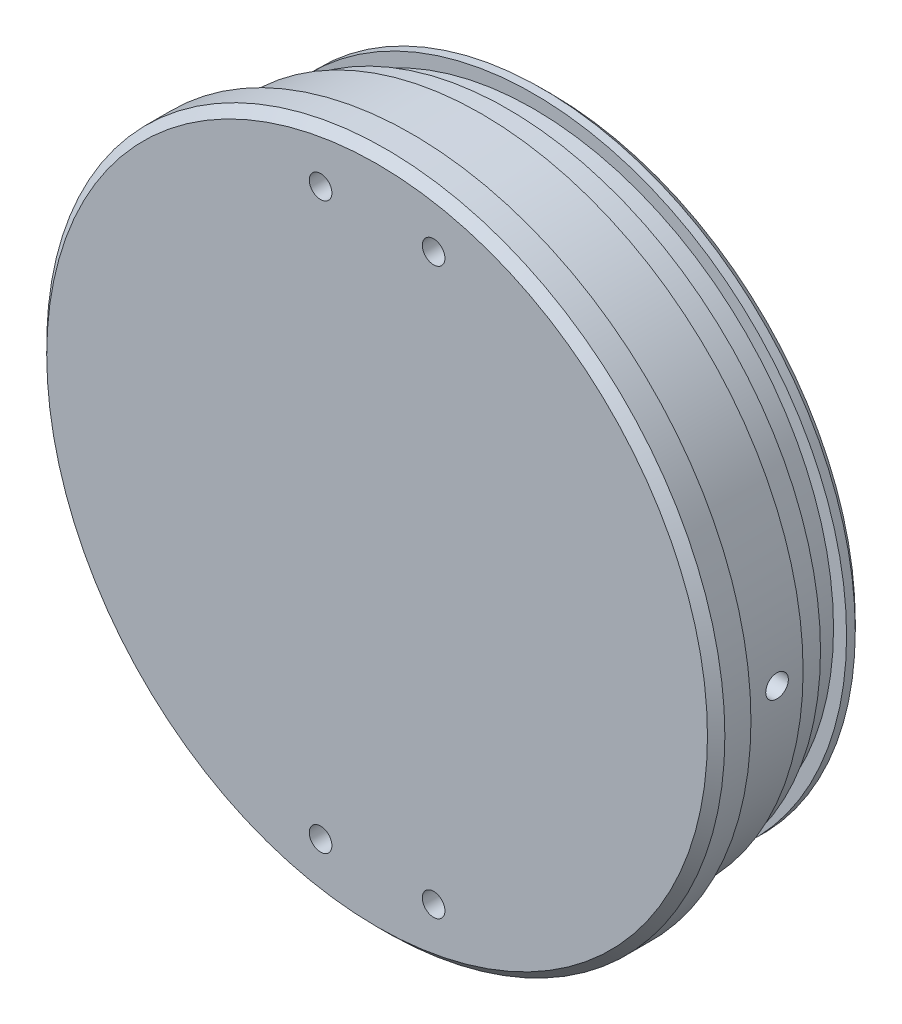
SolidWorks part; units mm, degrees
material "1060 Сплав"
ref_plane "Спереди" through (0, 0, 0) normal (0, 0, 1) x (1, 0, 0)
ref_plane "Сверху" through (0, 0, 0) normal (0, 1, 0) x (1, 0, 0)
ref_plane "Справа" through (0, 0, 0) normal (1, 0, 0) x (0, 0, -1)
sketch "Эскиз1" plane through (0, 0, 0) normal (0, 0, 1) x (1, 0, 0)
  circle A0 centre (0, 0) radius 39
  dimension "D1" = 78
extrude "Бобышка-Вытянуть1" add sketch "Эскиз1" along normal blind 4
sketch "Эскиз2" plane through (0, 0, 4) normal (0, 0, 1) x (1, 0, 0)
  line L0 (0, 40.548) -> (0, -43.3588) construction
sketch "Эскиз3" plane through (0, 0, 0) normal (0, 0, -1) x (-1, 0, 0)
  circle A0 centre (0, 0) radius 37
  dimension "D1" = 74
extrude "Бобышка-Вытянуть2" add sketch "Эскиз3" along normal blind 8
sketch "Эскиз4" plane through (0, 0, -8) normal (0, 0, -1) x (-1, 0, 0)
  circle A0 centre (0, 0) radius 36
  dimension "D1" = 72
extrude "Бобышка-Вытянуть3" add sketch "Эскиз4" along normal blind 8
sketch "Эскиз5" plane through (0, 0, 0) normal (1, 0, 0) x (0, 0, -1)
  line L0 (-46.651, 0) -> (48.0815, 0) construction
  line L1 (16, 36) -> (8, 36) construction
  line L2 (14, 36) -> (11, 36)
  line L3 (14, 36) -> (14, 34.5)
  line L4 (14, 34.5) -> (11, 34.5)
  line L5 (11, 36) -> (11, 34.5)
  line L6 (16, -36) -> (16, 36) construction
  dimension "D1" = 2
  dimension "D2" = 1.5
  dimension "D3" = 3
revolve "Вырез-Повернуть1" cut sketch "Эскиз5" angle 360 about L0
sketch "Эскиз7" plane through (0, 0, -16) normal (0, 0, -1) x (-1, 0, 0)
  circle A0 centre (0, 0) radius 27
  dimension "D1" = 54
extrude "Вырез-Вытянуть1" cut sketch "Эскиз7" against normal blind 17
chamfer "Фаска2" distance 1 angle 45 1 edges at (-36, 0, -16)
ref_plane "Плоскость6" through (37, 0, 0) normal (1, 0, 0) x (0, 0, -1)
sketch "Эскиз14" plane through (37, 0, 0) normal (1, 0, 0) x (0, 0, -1)
  line L0 (0, 0) -> (8.9796, 0) construction
  line L1 (8, -37) -> (8, 37) construction
  circle A0 centre (5, 0) radius 1.3
  dimension "D2" = 2.6
  dimension "D1" = 3
extrude "Вырез-Вытянуть4" cut sketch "Эскиз14" against normal blind 7
ref_plane "Плоскость7" through (-37, 0, 0) normal (1, 0, 0) x (0, 0, -1)
sketch "Эскиз16" plane through (-37, 0, 0) normal (1, 0, 0) x (0, 0, -1)
  line L0 (0, 0) -> (13.6916, 0) construction
  line L1 (8, -36) -> (8, 36) construction
  circle A0 centre (5, 0) radius 1.3
  dimension "D2" = 2.6
  dimension "D1" = 3
extrude "Вырез-Вытянуть5" cut sketch "Эскиз16" along normal blind 7
thread "Резьба1" pitch 0.3 start angle 0, offset 0, length 7, pitch 0.3, diameter 2.6
ref_plane "Плоскость8" through (37, 0, -3.7) normal (0, -1, 0) x (0, 0, 1)
sketch "Профиль резьбы1" plane through (37, 0, -3.7) normal (0, -1, 0) x (0, 0, 1)
  line L0 (0, 0) -> (0, 0.3) construction
  line L11 (0, 0.2625) -> (0, 0)
  line L12 (0, 0) -> (0.1624, 0.0938)
  line L13 (0.1624, 0.0938) -> (0.1624, 0.1688)
  line L15 (0.1624, 0.1688) -> (0, 0.2625)
  line L17 (0.1624, 0.1313) -> (0, 0.1313) construction
  point P3 (0, 0)
  dimension "Pitch" = 0.3
  dimension "Profile_Angle" = 60
  dimension "Profile_Land" = 0.075
  dimension "Profile_Height" = 0.1624
thread "Резьба2" pitch 0.3 start angle 0, offset 0, length 7, pitch 0.3, diameter 2.6
ref_plane "Плоскость9" through (-37, 0, -6.3) normal (0, -1, 0) x (0, 0, -1)
sketch "Профиль резьбы2" plane through (-37, 0, -6.3) normal (0, -1, 0) x (0, 0, -1)
  line L0 (0, 0) -> (0, 0.3) construction
  line L11 (0, 0.2625) -> (0, 0)
  line L12 (0, 0) -> (0.1624, 0.0938)
  line L13 (0.1624, 0.0938) -> (0.1624, 0.1688)
  line L15 (0.1624, 0.1688) -> (0, 0.2625)
  line L17 (0.1624, 0.1313) -> (0, 0.1313) construction
  point P3 (0, 0)
  dimension "Pitch" = 0.3
  dimension "Profile_Angle" = 60
  dimension "Profile_Land" = 0.075
  dimension "Profile_Height" = 0.1624
sketch "Эскиз18" plane through (0, 0, 4) normal (0, 0, 1) x (1, 0, 0)
  line L0 (0, 32.5) -> (12.4261, 32.5) construction
  line L1 (0, 46.4307) -> (0, -52.0425) construction
  line L2 (-51.6992, 0) -> (67.4175, 0) construction
  circle A0 centre (6.5, 32.5) radius 1.3
  circle A1 centre (-6.5, 32.5) radius 1.3
  circle A2 centre (6.5, -32.5) radius 1.3
  circle A3 centre (-6.5, -32.5) radius 1.3
  dimension "D1" = 2.6
  dimension "D2" = 6.5
extrude "Вырез-Вытянуть6" cut sketch "Эскиз18" against normal blind 7
chamfer "Фаска3" distance 1 angle 45 3 edges at (-27, 0, 1) (-27, 0, -16) (39, 0, 4)
